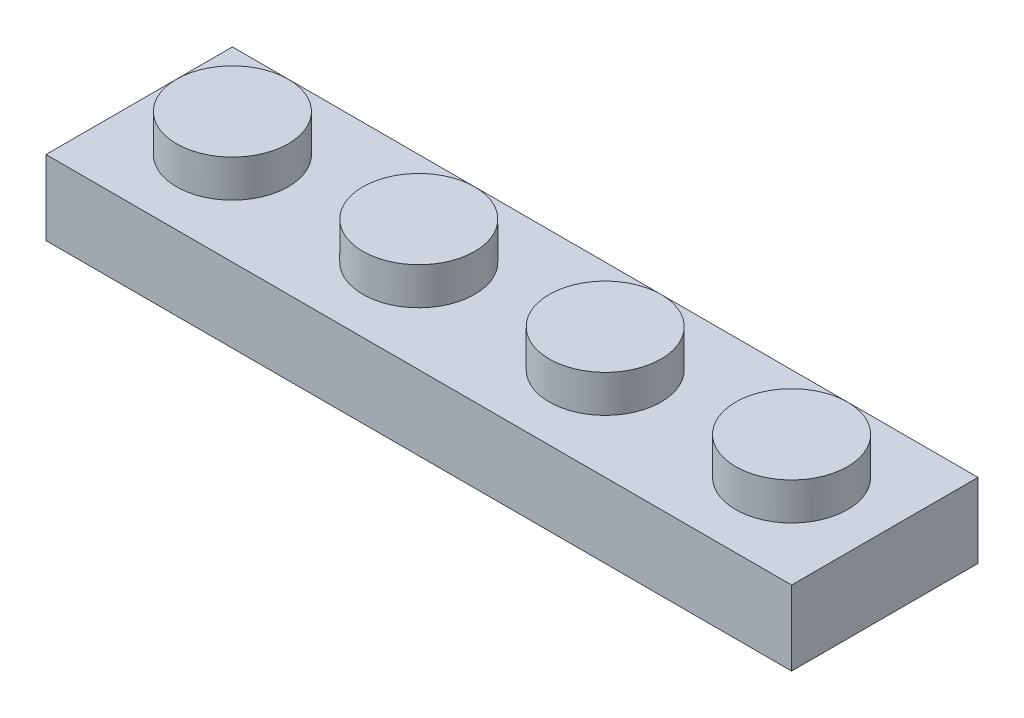
SolidWorks part; units mm, degrees
ref_plane "Front Plane" through (0, 0, 0) normal (0, 0, 1) x (1, 0, 0)
ref_plane "Top Plane" through (0, 0, 0) normal (0, 1, 0) x (1, 0, 0)
ref_plane "Right Plane" through (0, 0, 0) normal (1, 0, 0) x (0, 0, -1)
sketch "Sketch1" plane through (0, 0, 0) normal (0, 1, 0) x (1, 0, 0)
  line L1 (0, 0) -> (32, 0)
  line L2 (0, 0) -> (0, 8)
  line L3 (0, 8) -> (32, 8)
  line L4 (32, 0) -> (32, 8)
  dimension "D1" = 32
  dimension "D2" = 8
extrude "Boss-Extrude1" add sketch "Sketch1" along normal blind 3.2
sketch "Sketch2" plane through (0, 3.2, 0) normal (0, 1, 0) x (1, 0, 0)
  line L0 (16, 0) -> (16, 8) construction
  line L1 (0, 0) -> (32, 0) construction
  line L2 (32, 8) -> (0, 8) construction
  line L3 (32, 0) -> (32, 4) construction
  line L4 (32, 0) -> (32, 8) construction
  line L5 (32, 4) -> (28, 4) construction
  circle A0 centre (28, 4) radius 2.4
  dimension "D3" = 4.8
  dimension "D1" = 4
  dimension "D2" = 4
extrude "Boss-Extrude2" add sketch "Sketch2" along normal blind 1.6
pattern_linear "LPattern1" count 4 spacing 8 along (-1, 0, 0) of "Boss-Extrude2"
shell "Shell1" thickness 1.6
